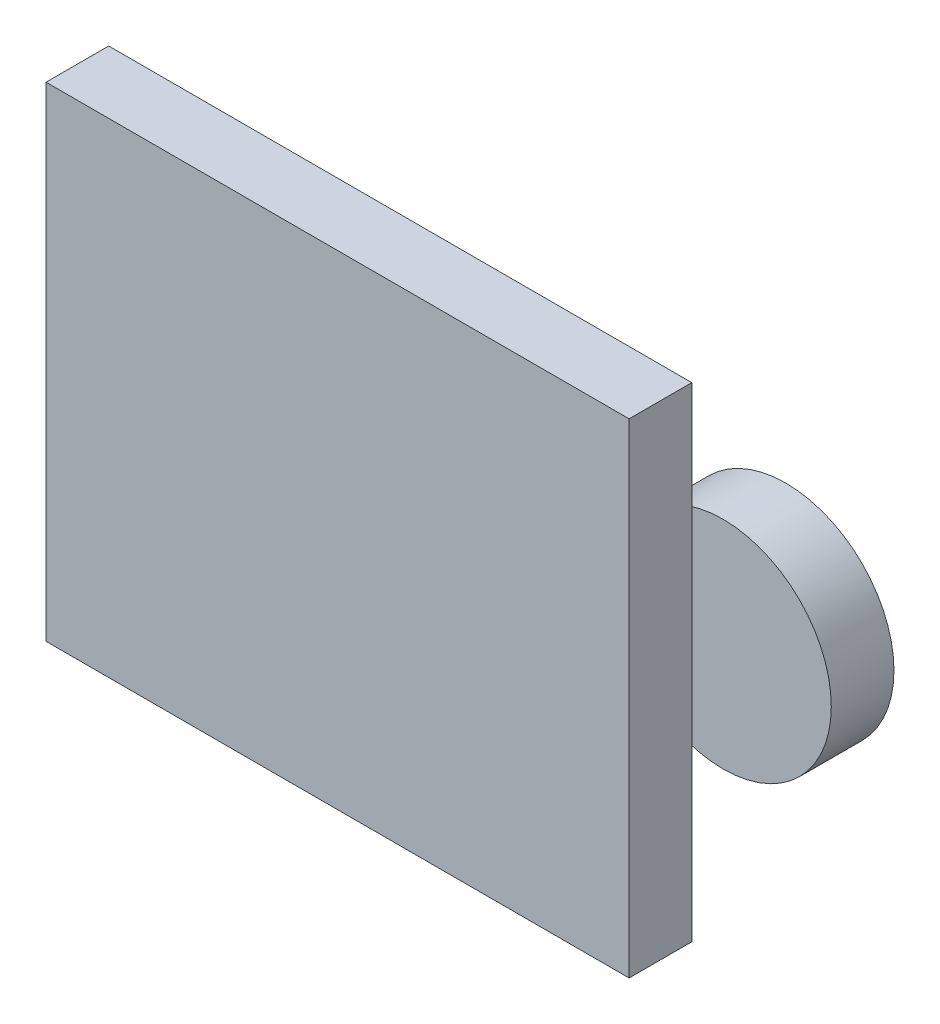
SolidWorks part; units mm, degrees
ref_plane "Спереди" through (0, 0, 0) normal (0, 0, 1) x (1, 0, 0)
ref_plane "Сверху" through (0, 0, 0) normal (0, 1, 0) x (1, 0, 0)
ref_plane "Справа" through (0, 0, 0) normal (1, 0, 0) x (0, 0, -1)
sketch "Эскиз1_fr" plane through (0, 0, 0) normal (0, 0, 1) x (1, 0, 0)
  line L1 (-48.994, 38.0205) -> (44.0482, 38.0205)
  line L2 (-48.994, 38.0205) -> (-48.994, -39.257)
  line L3 (-48.994, -39.257) -> (44.0482, -39.257)
  line L4 (44.0482, 38.0205) -> (44.0482, -39.257)
extrude "Бобышка-Вытянуть1" add sketch "Эскиз1_fr" along normal blind 10
ref_plane "Плоскость4" through (0, 0, -5) normal (0, 0, 1) x (1, 0, 0)
sketch "Эскиз5" plane through (0, 0, -5) normal (0, 0, 1) x (1, 0, 0)
  line L0 (44.0482, -39.257) -> (44.0482, 38.0205) construction
  circle A0 centre (44.0482, -0.6182) radius 17.2618
extrude "Бобышка-Вытянуть2" add sketch "Эскиз5" against normal blind 10 separate body
ref_plane "Плоскость5" through (0, 0, 20) normal (0, 0, 1) x (1, 0, 0)
